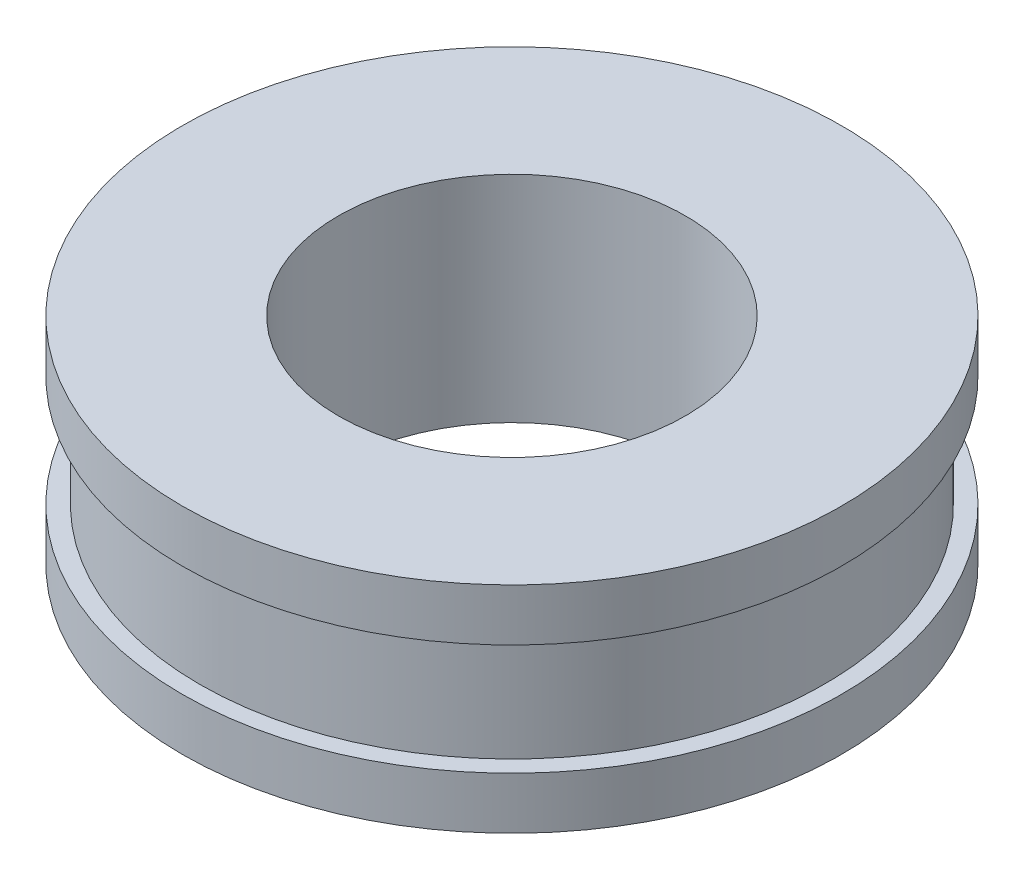
SolidWorks part; units mm, degrees
ref_plane "Front Plane" through (0, 0, 0) normal (0, 0, 1) x (1, 0, 0)
ref_plane "Top Plane" through (0, 0, 0) normal (0, 1, 0) x (1, 0, 0)
ref_plane "Right Plane" through (0, 0, 0) normal (1, 0, 0) x (0, 0, -1)
sketch "Sketch1" plane through (0, 0, 0) normal (0, 1, 0) x (1, 0, 0)
  circle A0 centre (0, 0) radius 47.5
  circle A1 centre (0, 0) radius 25
  dimension "D1" = 95
  dimension "D2" = 50
extrude "Boss-Extrude1" add sketch "Sketch1" along normal mid plane 31
sketch "Sketch3" plane through (0, 0, 0) normal (0, 1, 0) x (1, 0, 0)
  circle A0 centre (0, 0) radius 47.5
  circle A1 centre (0, 0) radius 45
  dimension "D1" = 95
  dimension "D2" = 90
extrude "Cut-Extrude1" cut sketch "Sketch3" against normal mid plane 16
